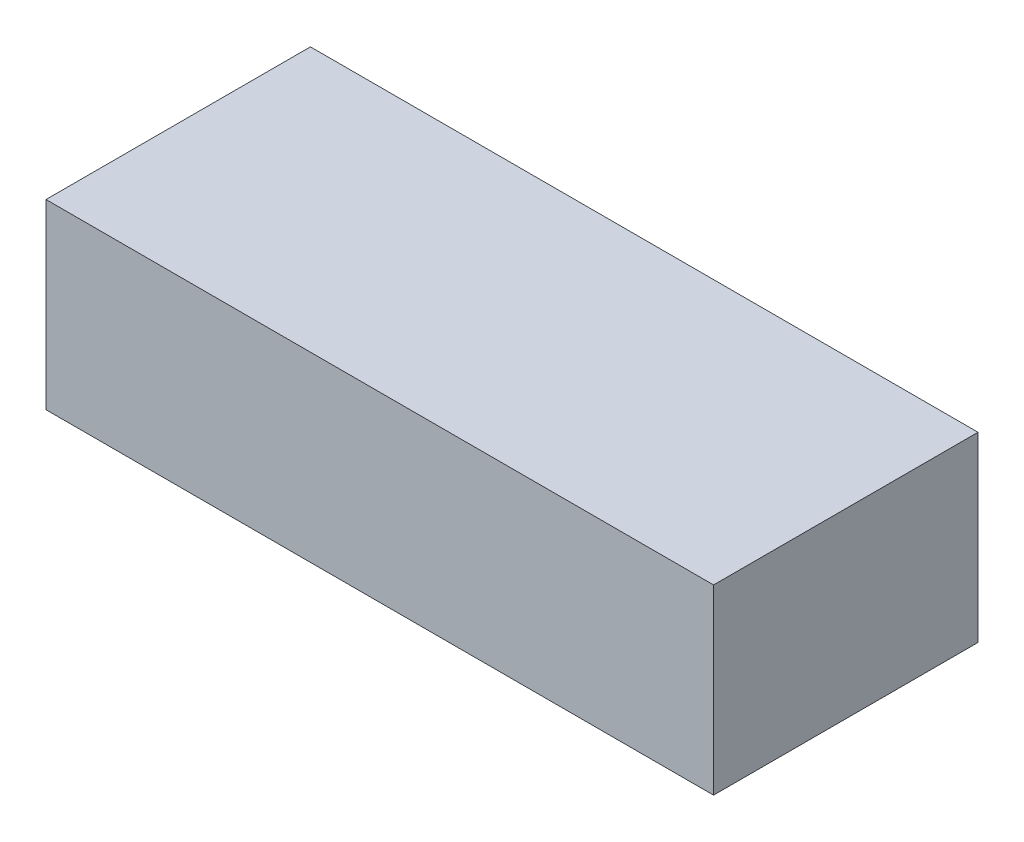
SolidWorks part; units mm, degrees
ref_plane "前视基准面" through (0, 0, 0) normal (0, 0, 1) x (1, 0, 0)
ref_plane "上视基准面" through (0, 0, 0) normal (0, 1, 0) x (1, 0, 0)
ref_plane "右视基准面" through (0, 0, 0) normal (1, 0, 0) x (0, 0, -1)
sketch "草图1" plane through (0, 0, 0) normal (0, 1, 0) x (1, 0, 0)
  line L1 (-38.5, 15.25) -> (38.5, 15.25)
  line L2 (-38.5, 15.25) -> (-38.5, -15.25)
  line L3 (-38.5, -15.25) -> (38.5, -15.25)
  line L4 (38.5, 15.25) -> (38.5, -15.25)
  line L5 (-38.5, 15.25) -> (38.5, -15.25) construction
  line L6 (-38.5, -15.25) -> (38.5, 15.25) construction
  point P0 (0, 0)
  dimension "D1" = 77
  dimension "D2" = 30.5
extrude "凸台-拉伸1" add sketch "草图1" along normal blind 21
